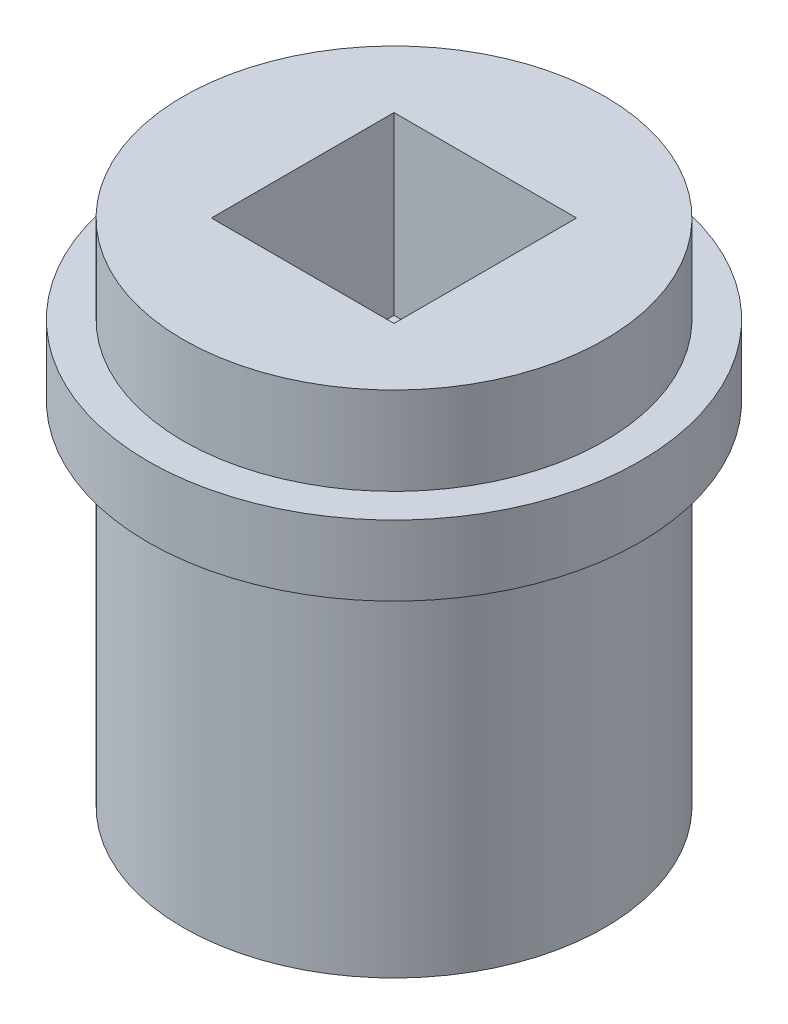
SolidWorks part; units mm, degrees
ref_plane "Ebene vorne" through (0, 0, 0) normal (0, 0, 1) x (1, 0, 0)
ref_plane "Ebene oben" through (0, 0, 0) normal (0, 1, 0) x (1, 0, 0)
ref_plane "Ebene rechts" through (0, 0, 0) normal (1, 0, 0) x (0, 0, -1)
sketch "Skizze1" plane through (0, 0, 0) normal (0, 1, 0) x (1, 0, 0)
  circle A0 centre (0, 0) radius 3
  dimension "D1" = 6
extrude "Aufsatz-Linear austragen1" add sketch "Skizze1" along normal blind 7.25
sketch "Skizze3" plane through (0, 0, 0) normal (0, 1, 0) x (1, 0, 0)
  circle A0 centre (0, 0) radius 3.5
  dimension "D1" = 7
extrude "Aufsatz-Linear austragen2" add sketch "Skizze3" along normal blind 1 from offset 5
sketch "Skizze2" plane through (0, 7.25, 0) normal (0, 1, 0) x (1, 0, 0)
  line L1 (-1.3, -1.3) -> (1.3, -1.3)
  line L2 (-1.3, -1.3) -> (-1.3, 1.3)
  line L3 (-1.3, 1.3) -> (1.3, 1.3)
  line L4 (1.3, -1.3) -> (1.3, 1.3)
  line L5 (-1.3, -1.3) -> (1.3, 1.3) construction
  line L6 (-1.3, 1.3) -> (1.3, -1.3) construction
  point P0 (0, 0)
  dimension "D1" = 2.6
  dimension "D2" = 2.6
extrude "Schnitt-Linear austragen1" cut sketch "Skizze2" against normal blind 2.5 contours L2 L1 L4 L3
